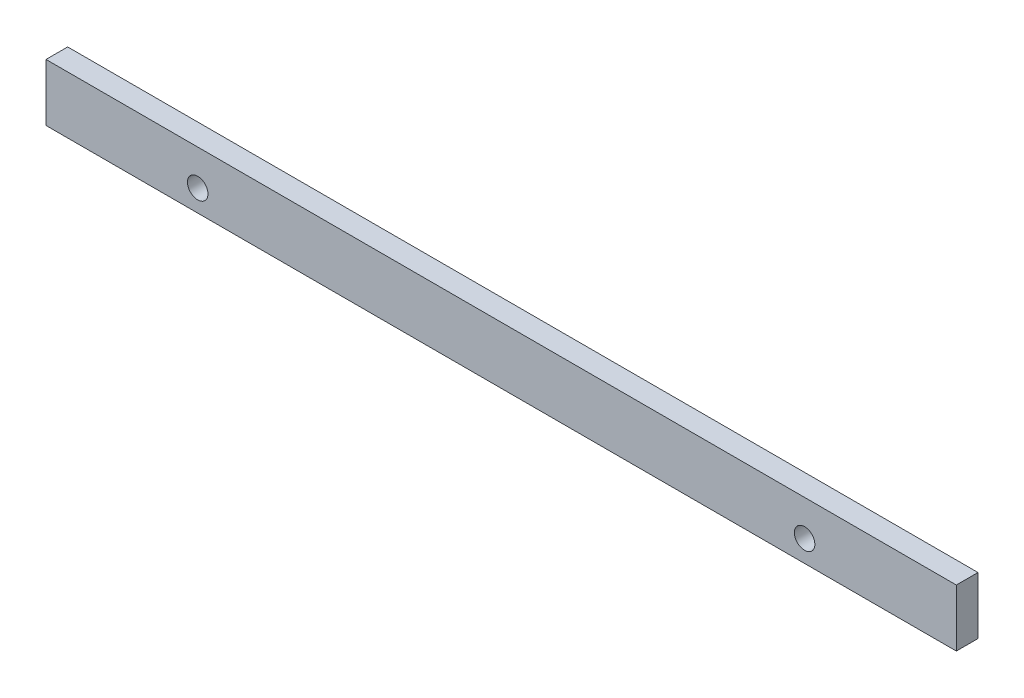
SolidWorks part; units mm, degrees
ref_plane "Front Plane" through (0, 0, 0) normal (0, 0, 1) x (1, 0, 0)
ref_plane "Top Plane" through (0, 0, 0) normal (0, 1, 0) x (1, 0, 0)
ref_plane "Right Plane" through (0, 0, 0) normal (1, 0, 0) x (0, 0, -1)
sketch "Sketch3" plane through (0, 0, 0) normal (0, 0, 1) x (1, 0, 0)
  line L0 (-44.45, -1.016) -> (44.45, -1.016) construction
  line L1 (66.675, 4.191) -> (-66.675, 4.191)
  line L2 (66.675, 4.191) -> (66.675, -4.191)
  line L3 (66.675, -4.191) -> (-66.675, -4.191)
  line L4 (-66.675, 4.191) -> (-66.675, -4.191)
  line L5 (66.675, 4.191) -> (-66.675, -4.191) construction
  line L6 (66.675, -4.191) -> (-66.675, 4.191) construction
  line L7 (-66.675, 4.191) -> (-69.85, 4.191)
  line L8 (-66.675, 4.191) -> (-66.675, -4.191)
  line L9 (-66.675, -4.191) -> (-69.85, -4.191)
  line L10 (-69.85, 4.191) -> (-69.85, -4.191)
  line L11 (66.675, 4.191) -> (69.85, 4.191)
  line L12 (66.675, 4.191) -> (66.675, -4.191)
  line L13 (66.675, -4.191) -> (69.85, -4.191)
  line L14 (69.85, 4.191) -> (69.85, -4.191)
  circle A0 centre (-44.45, -1.016) radius 1.5
  circle A1 centre (44.45, -1.016) radius 1.5
  point P0 (0, 0)
  point P14 (0, -1.016)
  dimension "D4" = 3
  dimension "D1" = 133.35
  dimension "D2" = 8.382
  dimension "D3" = 3.175
  dimension "D5" = 3.175
  dimension "D6" = 22.225
extrude "Boss-Extrude1" add sketch "Sketch3" along normal blind 3.175 contours L1 L4 L3 L2 A1 A0
